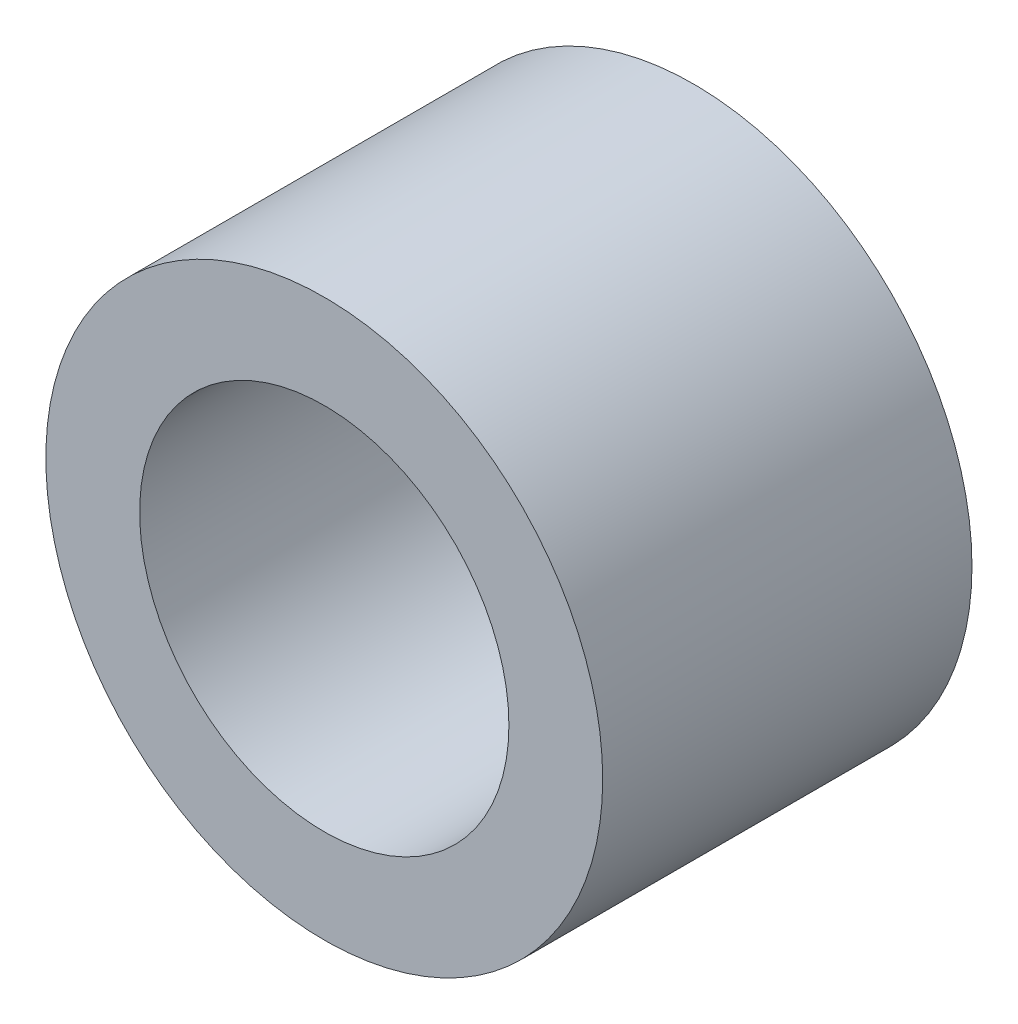
SolidWorks part; units mm, degrees
material "Plain Carbon Steel"
ref_plane "Front Plane" through (0, 0, 0) normal (0, 0, 1) x (1, 0, 0)
ref_plane "Top Plane" through (0, 0, 0) normal (0, 1, 0) x (1, 0, 0)
ref_plane "Right Plane" through (0, 0, 0) normal (1, 0, 0) x (0, 0, -1)
sketch "Sketch1" plane through (0, 0, 0) normal (0, 0, 1) x (1, 0, 0)
  circle A0 centre (0, 0) radius 4.7879
  circle A1 centre (0, 0) radius 3.175
  dimension "D1" = 9.5758
  dimension "ID" = 6.35
extrude "Extrude1" add sketch "Sketch1" along normal mid plane 6.35
sketch "Sketch2" plane through (0, 0, 0) normal (1, 0, 0) x (0, 0, -1)
  line L0 (-3.175, -3.175) -> (3.175, -3.175) construction
  line L3 (3.175, 3.175) -> (-3.175, 3.175) construction
  line L5 (-3.175, -3.175) -> (3.175, -3.175)
  line L6 (3.175, 3.175) -> (-3.175, 3.175)
sketch "Sketch4" plane through (0, 0, 3.175) normal (0, 0, 1) x (1, 0, 0)
  line L0 (0, 0) -> (-2.2451, 2.2451)
  line L1 (0, -15.7442) -> (0, 15.7442) construction
  circle A0 centre (0, 0) radius 3.175 construction
  dimension "D1" = 45
